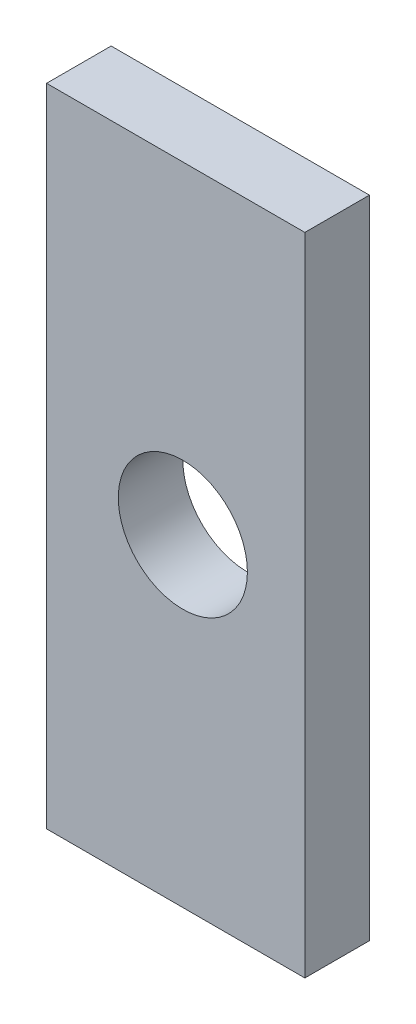
SolidWorks part; units mm, degrees
material "Plain Carbon Steel"
ref_plane "Front Plane" through (0, 0, 0) normal (0, 0, 1) x (1, 0, 0)
ref_plane "Top Plane" through (0, 0, 0) normal (0, 1, 0) x (1, 0, 0)
ref_plane "Right Plane" through (0, 0, 0) normal (1, 0, 0) x (0, 0, -1)
sketch "Sketch1" plane through (0, 0, 0) normal (0, 0, 1) x (1, 0, 0)
  line L0 (-211.5251, -167.4874) -> (-224.2251, -167.4874)
  line L1 (-224.2251, -167.4874) -> (-224.2251, -199.2374)
  line L2 (-224.2251, -199.2374) -> (-211.5251, -199.2374)
  line L3 (-211.5251, -185.6034) -> (-211.5251, -220.6034) construction
  line L4 (-211.5251, -199.2374) -> (-211.5251, -167.4874)
  line L5 (-224.2251, -183.3624) -> (-211.5251, -183.3624) construction
  circle A0 centre (-217.5251, -183.3624) radius 3.175
  dimension "D1" = 6.35
  dimension "D2" = 12.7
  dimension "D3" = 31.75
extrude "Boss-Extrude1" add sketch "Sketch1" against normal blind 3.175
